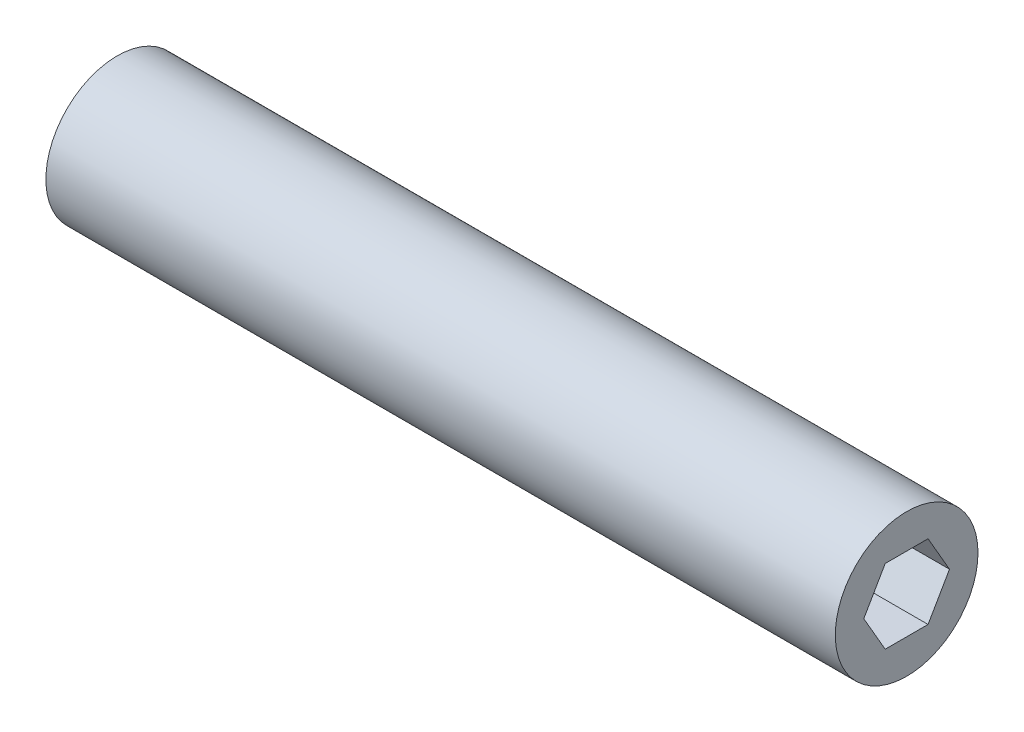
SolidWorks part; units mm, degrees
ref_plane "Front Plane" through (0, 0, 0) normal (0, 0, 1) x (1, 0, 0)
ref_plane "Top Plane" through (0, 0, 0) normal (0, 1, 0) x (1, 0, 0)
ref_plane "Right Plane" through (0, 0, 0) normal (1, 0, 0) x (0, 0, -1)
sketch "Sketch1" plane through (0, 0, 0) normal (1, 0, 0) x (0, 0, -1)
  line L1 (7.6256, 0) -> (3.8128, 6.604)
  line L2 (3.8128, 6.604) -> (-3.8128, 6.604)
  line L3 (-3.8128, 6.604) -> (-7.6256, 0)
  line L4 (-7.6256, 0) -> (-3.8128, -6.604)
  line L5 (-3.8128, -6.604) -> (3.8128, -6.604)
  line L6 (3.8128, -6.604) -> (7.6256, 0)
  circle A0 centre (0, 0) radius 6.604 construction
  circle A1 centre (0, 0) radius 12.7
  dimension "D1" = 13.208
  dimension "D2" = 25.4
extrude "Boss-Extrude1" add sketch "Sketch1" along normal blind 140.4938
